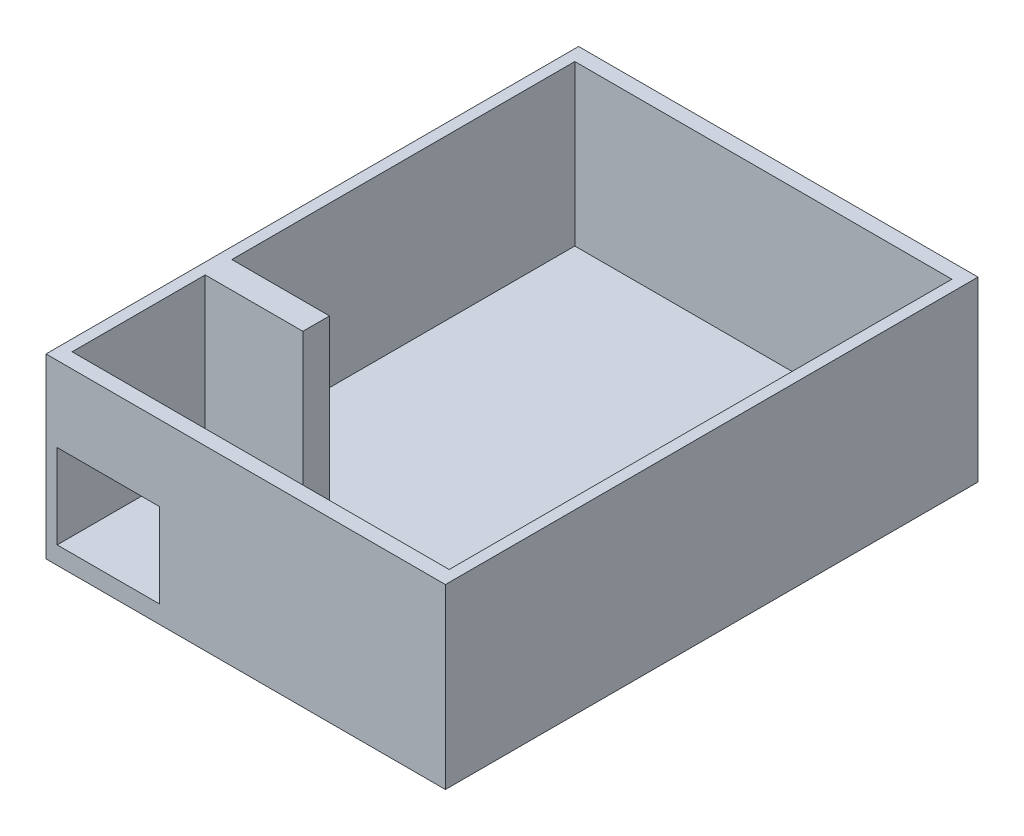
SolidWorks part; units mm, degrees
ref_plane "Ön Düzlem" through (0, 0, 0) normal (0, 0, 1) x (1, 0, 0)
ref_plane "Üst Düzlem" through (0, 0, 0) normal (0, 1, 0) x (1, 0, 0)
ref_plane "Sağ Düzlem" through (0, 0, 0) normal (1, 0, 0) x (0, 0, -1)
sketch "Çizim1" plane through (0, 0, 0) normal (0, 1, 0) x (1, 0, 0)
  line L1 (-22.5, 30) -> (22.5, 30)
  line L2 (-22.5, 30) -> (-22.5, -30)
  line L3 (-22.5, -30) -> (22.5, -30)
  line L4 (22.5, 30) -> (22.5, -30)
  line L5 (-22.5, 30) -> (22.5, -30) construction
  line L6 (-22.5, -30) -> (22.5, 30) construction
  point P0 (0, 0)
extrude "Yükseklik-Ekstrüzyon1" add sketch "Çizim1" along normal blind 2
sketch "Çizim2" plane through (0, 2, 0) normal (0, 1, 0) x (1, 0, 0)
  line L1 (-22.5, -30) -> (22.5, -30)
  line L2 (-22.5, -30) -> (-22.5, 30)
  line L3 (-22.5, 30) -> (22.5, 30)
  line L4 (22.5, -30) -> (22.5, 30)
  line L5 (-22.5, -30) -> (22.5, 30) construction
  line L6 (-22.5, 30) -> (22.5, -30) construction
  line L7 (21.24, -28.32) -> (-21.24, -28.32)
  line L8 (21.24, -28.32) -> (21.24, 28.32)
  line L9 (21.24, 28.32) -> (-21.24, 28.32)
  line L10 (-21.24, -28.32) -> (-21.24, 28.32)
  line L11 (21.24, -28.32) -> (-21.24, 28.32) construction
  line L12 (21.24, 28.32) -> (-21.24, -28.32) construction
  point P0 (0, 0)
  point P5 (0, 0)
extrude "Yükseklik-Ekstrüzyon2" add sketch "Çizim2" along normal blind 18
sketch "Çizim6" plane through (0, 0, 30) normal (0, 0, 1) x (1, 0, 0)
  line L2 (-21.24, 11.5) -> (-21.24, 2)
  line L3 (-21.24, 2) -> (-9.74, 2)
  line L4 (-9.74, 2) -> (-9.74, 11.5)
  line L5 (-9.74, 11.5) -> (-21.24, 11.5)
extrude "Kes-Ekstrüzyon2" cut sketch "Çizim6" against normal blind 18
sketch "Çizim7" plane through (0, 2, 0) normal (0, 1, 0) x (1, 0, 0)
  line L1 (-21.24, 28.32) -> (-21.24, -28.32) construction
  line L2 (-21.24, -13.32) -> (-10.24, -13.32)
  line L3 (-10.24, -13.32) -> (-10.24, -10.32)
  line L4 (-10.24, -10.32) -> (-21.24, -10.32)
  line L5 (-21.24, 28.32) -> (-21.24, -30) construction
  line L6 (-21.24, -10.32) -> (-21.24, -13.32)
extrude "Yükseklik-Ekstrüzyon3" add sketch "Çizim7" along normal blind 18
